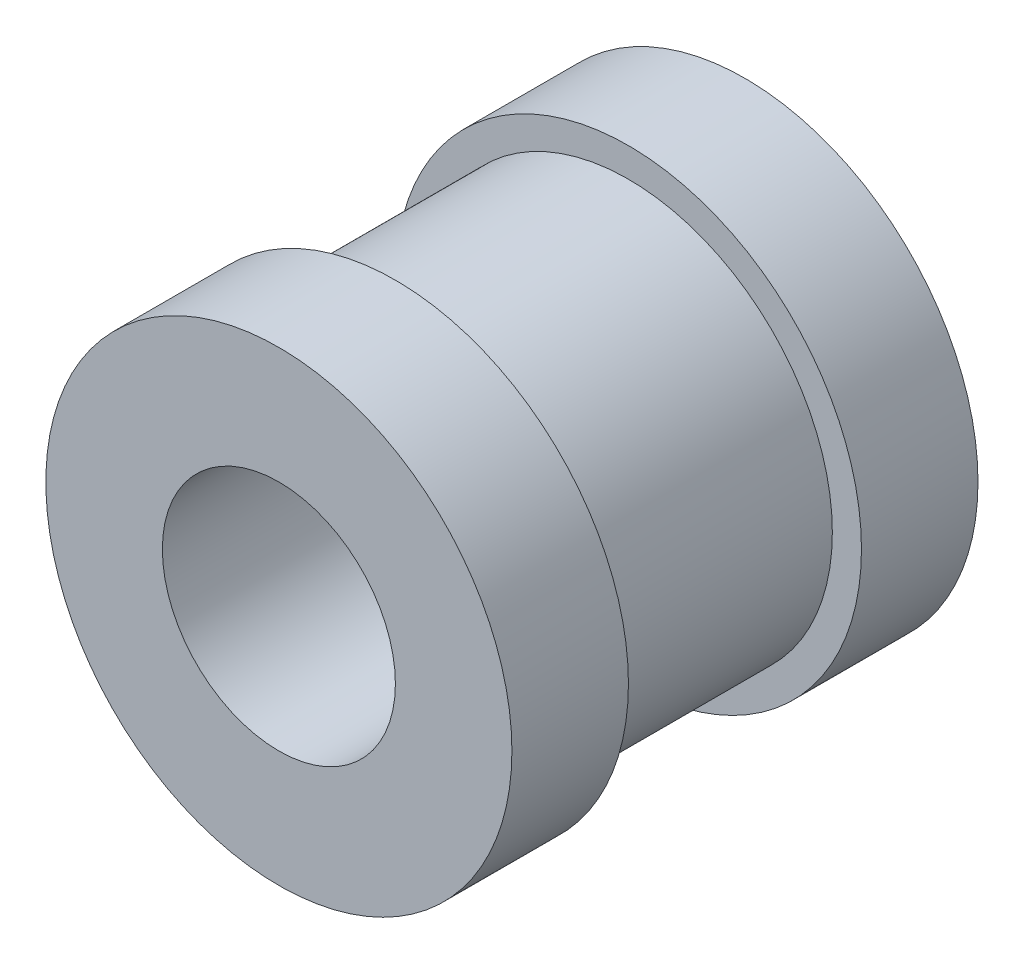
SolidWorks part; units mm, degrees
material "PE High Density"
ref_plane "Front Plane" through (0, 0, 0) normal (0, 0, 1) x (1, 0, 0)
ref_plane "Top Plane" through (0, 0, 0) normal (0, 1, 0) x (1, 0, 0)
ref_plane "Right Plane" through (0, 0, 0) normal (1, 0, 0) x (0, 0, -1)
sketch "Sketch1" plane through (0, 0, 0) normal (0, 0, 1) x (1, 0, 0)
  circle A0 centre (0, 0) radius 10
  dimension "D1" = 20
extrude "Boss-Extrude1" add sketch "Sketch1" along normal blind 5
sketch "Sketch2" plane through (0, 0, 5) normal (0, 0, 1) x (1, 0, 0)
  circle A0 centre (0, 0) radius 8.75
  dimension "D1" = 17.5
extrude "Boss-Extrude2" add sketch "Sketch2" along normal blind 10
sketch "Sketch3" plane through (0, 0, 15) normal (0, 0, 1) x (1, 0, 0)
  circle A1 centre (0, 0) radius 8.75
  circle A2 centre (0, 0) radius 8.75
  circle A3 centre (0, 0) radius 10
  circle A4 centre (0, 0) radius 10
  dimension "D1" = 0
  dimension "D2" = 0
extrude "Boss-Extrude3" add sketch "Sketch3" along normal blind 5 contours A4
sketch "Sketch4" plane through (0, 0, 20) normal (0, 0, 1) x (1, 0, 0)
  circle A0 centre (0, 0) radius 5
  dimension "D1" = 10
extrude "Cut-Extrude1" cut sketch "Sketch4" against normal through all
